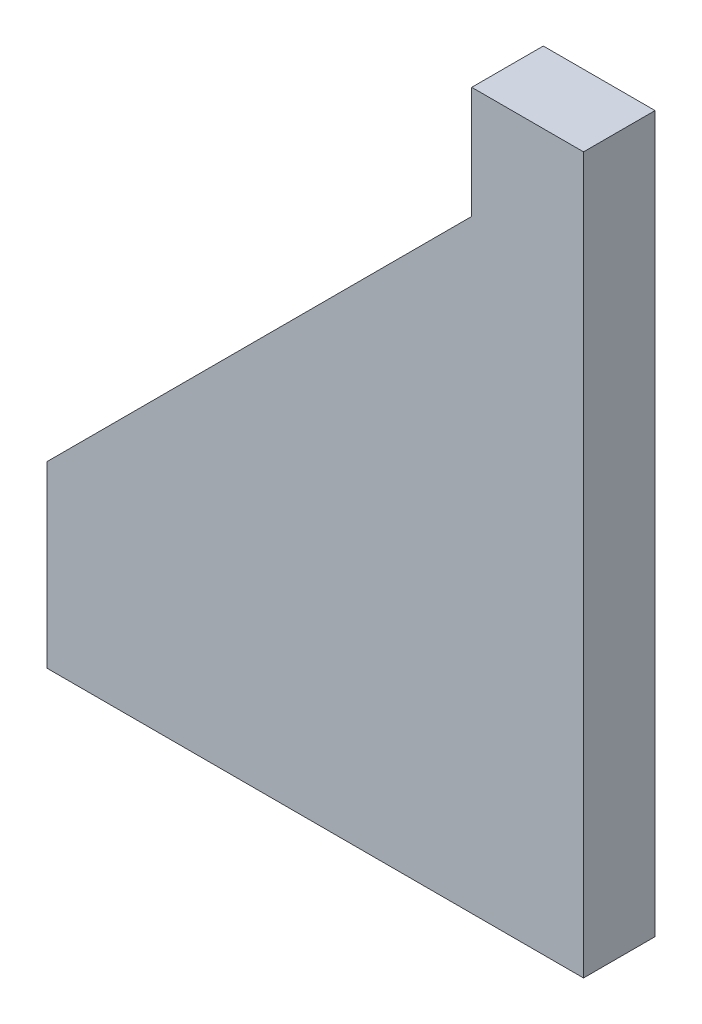
SolidWorks part; units mm, degrees
ref_plane "Alzado" through (0, 0, 0) normal (0, 0, 1) x (1, 0, 0)
ref_plane "Planta" through (0, 0, 0) normal (0, 1, 0) x (1, 0, 0)
ref_plane "Vista lateral" through (0, 0, 0) normal (1, 0, 0) x (0, 0, -1)
sketch "Croquis1" plane through (0, 0, 0) normal (0, 0, 1) x (1, 0, 0)
  line L0 (-253.1286, -55.1583) -> (46.8714, -55.1583)
  line L1 (46.8714, -55.1583) -> (46.8714, 344.8417)
  line L2 (-253.1286, -55.1583) -> (-253.1286, 44.8417)
  line L3 (46.8714, 344.8417) -> (-15.6286, 344.8417)
  line L4 (-253.1286, 44.8417) -> (-15.6286, 282.3417)
  line L5 (-15.6286, 282.3417) -> (-15.6286, 344.8417)
  line L6 (-84.0157, -55.1583) -> (-31.406, -55.1583)
  dimension "D1" = 400
  dimension "D2" = 300
  dimension "D3" = 100
  dimension "D4" = 62.5
  dimension "D5" = 62.5
extrude "Saliente-Extruir2" add sketch "Croquis1" along normal blind 40 contours L5 L4 L2 L0 L1 L3
